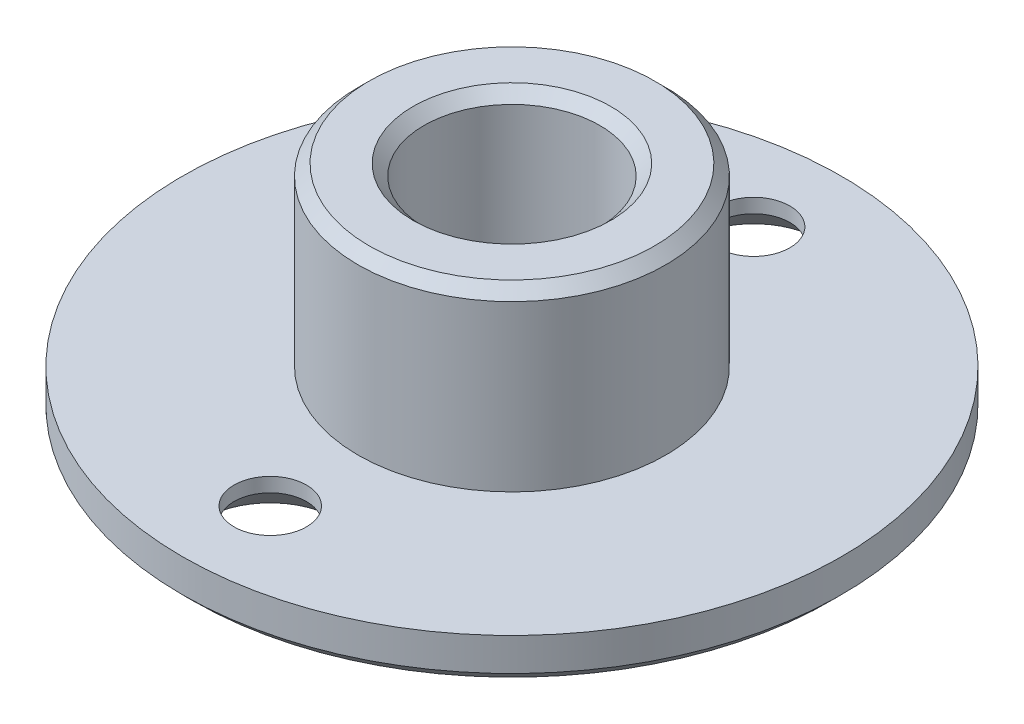
SolidWorks part; units mm, degrees
ref_plane "前视基准面" through (0, 0, 0) normal (0, 0, 1) x (1, 0, 0)
ref_plane "上视基准面" through (0, 0, 0) normal (0, 1, 0) x (1, 0, 0)
ref_plane "右视基准面" through (0, 0, 0) normal (1, 0, 0) x (0, 0, -1)
sketch "草图1" plane through (0, 0, 0) normal (0, 1, 0) x (1, 0, 0)
  circle A0 centre (0, 0) radius 15
  dimension "D1" = 30
extrude "凸台-拉伸1" add sketch "草图1" along normal blind 2
sketch "草图2" plane through (0, 2, 0) normal (0, 1, 0) x (1, 0, 0)
  circle A0 centre (0, 0) radius 7
  dimension "D1" = 14
extrude "凸台-拉伸2" add sketch "草图2" along normal blind 8
hole_wizard "Ø8.0mm 暗销孔1" positions "3D草图1" profile "草图4" hole size "Ø8.0" standard "GB" end condition through all
sketch3d "3D草图1"
  circle A0 centre (0, 10, 0) radius 7 construction
  point P0 (0, 10, 0)
  point P5 (0, 17, 0)
sketch "草图4" plane through (0, 10, 0) normal (1, 0, 0) x (0, 0, 1)
  line L0 (0, 0) -> (0, 10)
  line L1 (0, 10) -> (4, 10)
  line L2 (4, 10) -> (4, 0)
  line L5 (4, 0) -> (0, 0)
  line L11 (0, -6.35) -> (0, 107.95) construction
  dimension "通孔孔直径" = 8
  dimension "通孔孔深度" = 10
sketch "草图5" plane through (0, 0, 0) normal (0, -1, 0) x (1, 0, 0)
  line L0 (0, 0) -> (0, -11) construction
  circle A0 centre (0, 0) radius 11
  dimension "D1" = 22
hole_wizard "M6 内六角花形半沉头螺钉的锥形沉头孔1" positions "3D草图2" profile "草图6" countersink size "M6" standard "GB" end condition through all
sketch3d "3D草图2"
  point P0 (0, 0, -11)
sketch "草图6" plane through (0, 0, -11) normal (1, 0, 0) x (0, 0, -1)
  line L0 (0, 0) -> (0, 10)
  line L1 (0, 10) -> (1.65, 10)
  line L2 (1.65, 10) -> (1.65, 1.35)
  line L3 (1.65, 1.35) -> (3, 0)
  line L5 (3, 0) -> (0, 0)
  line L6 (-1.65, 1.35) -> (-3, 0) construction
  line L11 (0, -6.35) -> (0, 107.95) construction
  dimension "通孔孔直径" = 3.3
  dimension "通孔孔深度" = 10
  dimension "近端锥形沉头孔直径" = 6
  dimension "近端锥形沉头孔角度" = 90
mirror "镜向1" about plane through (0, 0, 0) normal (0, 0, 1) of "M6 内六角花形半沉头螺钉的锥形沉头孔1"
chamfer "倒角1" distance 0.5 angle 45 4 edges at (0, 0, 4) (0, 0, 15) (0, 10, 4) (0, 10, 7)
